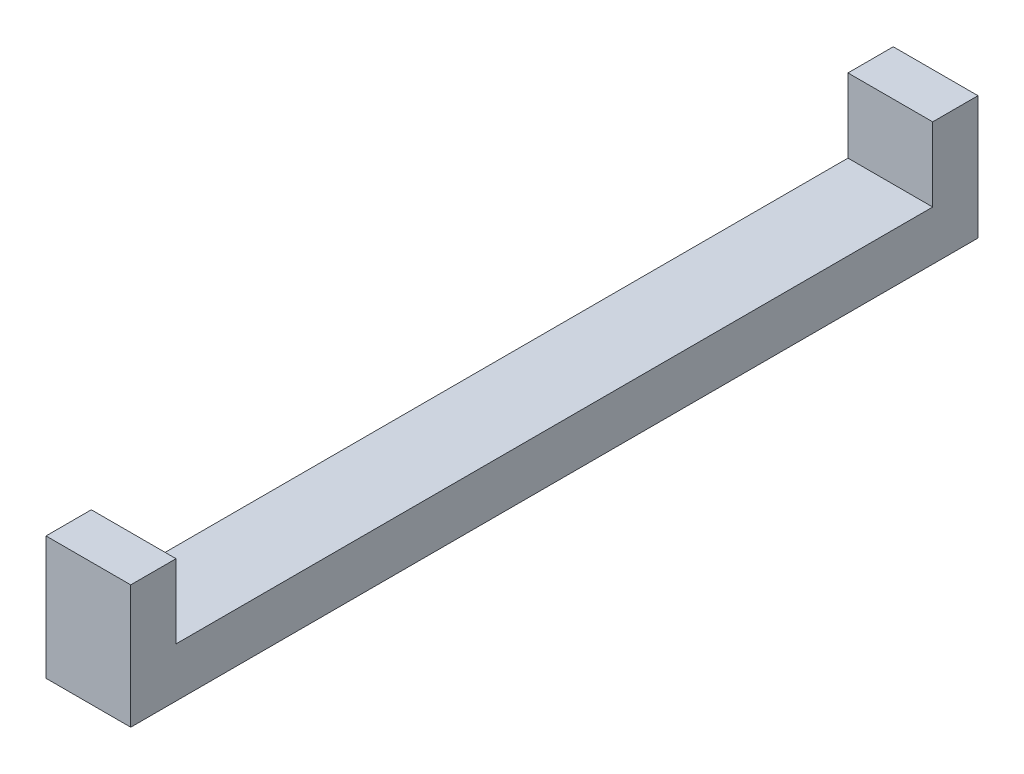
SolidWorks part; units mm, degrees
ref_plane "정면" through (0, 0, 0) normal (0, 0, 1) x (1, 0, 0)
ref_plane "윗면" through (0, 0, 0) normal (0, 1, 0) x (1, 0, 0)
ref_plane "우측면" through (0, 0, 0) normal (1, 0, 0) x (0, 0, -1)
sketch "스케치1" plane through (0, 0, 0) normal (1, 0, 0) x (0, 0, -1)
  line L0 (50, 0) -> (-50, 0)
  line L1 (-50, 0) -> (-50, 14.5559)
  line L2 (-50, 14.5559) -> (-44.6521, 14.5559)
  line L3 (-44.6521, 14.5559) -> (-44.6521, 5.8469)
  line L4 (-44.6521, 5.8469) -> (44.6521, 5.8469)
  line L5 (0, 5.8469) -> (0, 0) construction
  line L6 (44.6521, 14.5559) -> (44.6521, 5.8469)
  line L7 (50, 14.5559) -> (44.6521, 14.5559)
  line L8 (50, 0) -> (50, 14.5559)
  dimension "D1" = 100
extrude "보스-돌출1" add sketch "스케치1" along normal mid plane 10
